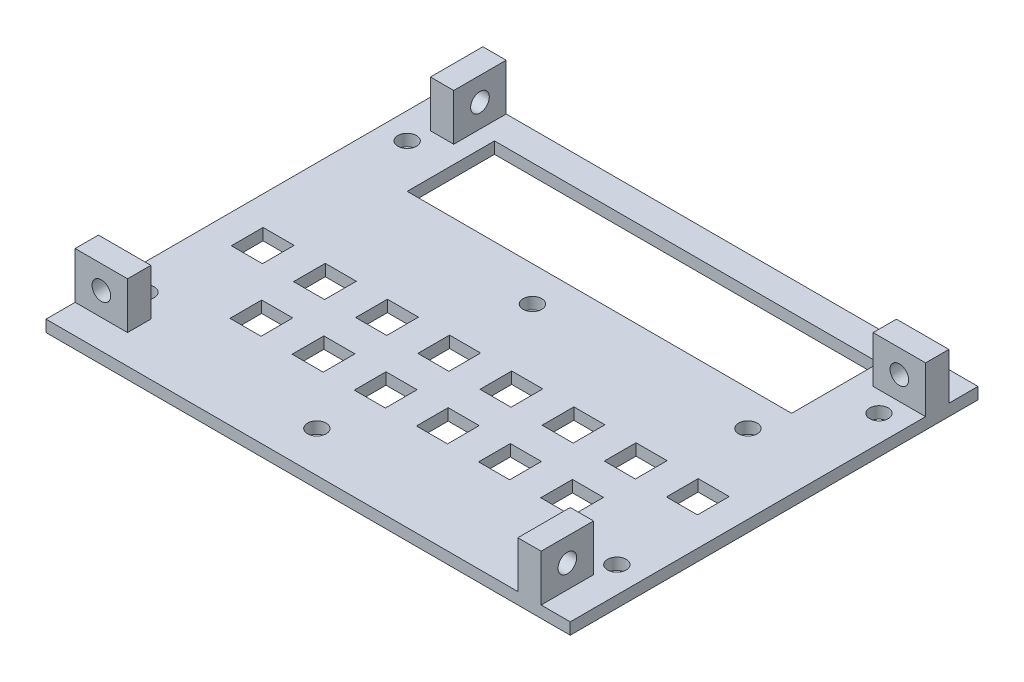
SolidWorks part; units mm, degrees
ref_plane "Plano frontal" through (0, 0, 0) normal (0, 0, 1) x (1, 0, 0)
ref_plane "Plano superior" through (0, 0, 0) normal (0, 1, 0) x (1, 0, 0)
ref_plane "Plano direito" through (0, 0, 0) normal (1, 0, 0) x (0, 0, -1)
sketch "Esboço1" plane through (0, 0, 0) normal (0, 1, 0) x (1, 0, 0)
  line L1 (-45, -35) -> (45, -35)
  line L2 (-45, -35) -> (-45, 35)
  line L3 (-45, 35) -> (45, 35)
  line L4 (45, -35) -> (45, 35)
  line L5 (-45, -35) -> (45, 35) construction
  line L6 (-45, 35) -> (45, -35) construction
  point P0 (0, 0)
  dimension "D1" = 90
  dimension "D2" = 70
extrude "Ressalto-extrusão1" add sketch "Esboço1" along normal blind 2
sketch "Esboço2" plane through (0, 2, 0) normal (0, 1, 0) x (1, 0, 0)
  line L104 (-29.33, -2.73) -> (-29.33, -8.18)
  line L105 (-23.996, -2.73) -> (-23.996, -8.18)
  line L106 (-29.33, -2.73) -> (-23.996, -2.73)
  line L107 (-29.33, -8.18) -> (-23.996, -8.18)
  line L108 (-18.66, -2.73) -> (-18.66, -8.18)
  line L109 (-13.326, -2.73) -> (-13.326, -8.18)
  line L110 (-18.66, -2.73) -> (-13.326, -2.73)
  line L111 (-18.66, -8.18) -> (-13.326, -8.18)
  line L112 (-7.99, -2.73) -> (-7.99, -8.18)
  line L113 (-2.656, -2.73) -> (-2.656, -8.18)
  line L114 (-7.99, -2.73) -> (-2.656, -2.73)
  line L115 (-7.99, -8.18) -> (-2.656, -8.18)
  line L116 (2.68, -2.73) -> (2.68, -8.18)
  line L117 (8.014, -2.73) -> (8.014, -8.18)
  line L118 (2.68, -2.73) -> (8.014, -2.73)
  line L119 (2.68, -8.18) -> (8.014, -8.18)
  line L120 (13.35, -2.73) -> (13.35, -8.18)
  line L121 (18.684, -2.73) -> (18.684, -8.18)
  line L122 (13.35, -2.73) -> (18.684, -2.73)
  line L123 (13.35, -8.18) -> (18.684, -8.18)
  line L124 (24.02, -2.73) -> (24.02, -8.18)
  line L125 (29.354, -2.73) -> (29.354, -8.18)
  line L126 (24.02, -2.73) -> (29.354, -2.73)
  line L127 (24.02, -8.18) -> (29.354, -8.18)
  line L128 (34.69, -2.73) -> (34.69, -8.18)
  line L129 (40.024, -2.73) -> (40.024, -8.18)
  line L130 (34.69, -2.73) -> (40.024, -2.73)
  line L131 (34.69, -8.18) -> (40.024, -8.18)
  line L132 (-29.33, -13.64) -> (-29.33, -19.09)
  line L133 (-23.996, -13.64) -> (-23.996, -19.09)
  line L134 (-29.33, -13.64) -> (-23.996, -13.64)
  line L135 (-29.33, -19.09) -> (-23.996, -19.09)
  line L136 (-18.66, -13.64) -> (-18.66, -19.09)
  line L137 (-13.326, -13.64) -> (-13.326, -19.09)
  line L138 (-18.66, -13.64) -> (-13.326, -13.64)
  line L139 (-18.66, -19.09) -> (-13.326, -19.09)
  line L140 (-7.99, -13.64) -> (-7.99, -19.09)
  line L141 (-2.656, -13.64) -> (-2.656, -19.09)
  line L142 (-7.99, -13.64) -> (-2.656, -13.64)
  line L143 (-7.99, -19.09) -> (-2.656, -19.09)
  line L144 (2.68, -13.64) -> (2.68, -19.09)
  line L145 (8.014, -13.64) -> (8.014, -19.09)
  line L146 (2.68, -13.64) -> (8.014, -13.64)
  line L147 (2.68, -19.09) -> (8.014, -19.09)
  line L148 (13.35, -13.64) -> (13.35, -19.09)
  line L149 (18.684, -13.64) -> (18.684, -19.09)
  line L150 (13.35, -13.64) -> (18.684, -13.64)
  line L151 (13.35, -19.09) -> (18.684, -19.09)
  line L152 (24.02, -13.64) -> (24.02, -19.09)
  line L153 (29.354, -13.64) -> (29.354, -19.09)
  line L154 (24.02, -13.64) -> (29.354, -13.64)
  line L155 (24.02, -19.09) -> (29.354, -19.09)
  line L196 (-40, -2.73) -> (-40, -8.18)
  line L197 (-34.666, -2.73) -> (-34.666, -8.18)
  line L198 (-40, -2.73) -> (-34.666, -2.73)
  line L199 (-40, -8.18) -> (-34.666, -8.18)
  point P0 (0, 0)
sketch "Esboço3" plane through (0, 2, 0) normal (0, 1, 0) x (1, 0, 0)
  line L5 (-40, 35) -> (-36, 35)
  line L7 (-40, 26) -> (-36, 26)
  line L8 (-36, 35) -> (-36, 26)
  line L42 (45, 30) -> (45, 26)
  line L43 (45, 26) -> (36, 26)
  line L44 (36, 30) -> (36, 26)
  line L51 (40, -26) -> (36, -26)
  line L52 (36, -35) -> (36, -26)
  line L58 (-45, -30) -> (-45, -26)
  line L59 (-45, -26) -> (-36, -26)
  line L60 (-36, -30) -> (-36, -26)
  line L63 (36, -35) -> (40, -35)
  line L68 (-40, 26) -> (-40, 35)
  line L69 (-36, -30) -> (-45, -30)
  line L70 (-45, -35) -> (45, -35) construction
  line L71 (40, -26) -> (40, -35)
  line L72 (45, -35) -> (45, 35) construction
  line L73 (36, 30) -> (45, 30)
  line L74 (45, 35) -> (-45, 35) construction
  dimension "D2" = 4
  dimension "D3" = 9
  dimension "D4" = 4
  dimension "D5" = 5
  dimension "D6" = 4
  dimension "D7" = 9
  dimension "D8" = 5
  dimension "D9" = 9
  dimension "D10" = 5
  dimension "D11" = 5
  dimension "D12" = 4
  dimension "D13" = 9
extrude "Ressalto-extrusão4" add sketch "Esboço3" along normal blind 8
sketch "Esboço6" plane through (0, 0, 0) normal (0, -1, 0) x (1, 0, 0)
  line L0 (0, 0) -> (0, -35) construction
  line L1 (45, -35) -> (-45, -35) construction
  line L3 (33, -30) -> (-33, -30)
  line L4 (33, -30) -> (33, -15)
  line L5 (33, -15) -> (-33, -15)
  line L6 (-33, -30) -> (-33, -15)
  line L7 (33, -30) -> (-33, -15) construction
  line L8 (33, -15) -> (-33, -30) construction
  point P5 (0, -22.5)
  dimension "D1" = 15
  dimension "D2" = 66
  dimension "D3" = 5
extrude "Corte-extrusão4" cut sketch "Esboço6" against normal blind 3
sketch "Esboço7" plane through (0, 2, 0) normal (0, 1, 0) x (1, 0, 0)
  line L1 (45, -35) -> (45, 26) construction
  line L3 (45, 35) -> (-36, 35) construction
  line L4 (31.5, 9) -> (-5.5, 9) construction
  line L5 (-5.5, 9) -> (-5.5, -28) construction
  line L6 (-5.5, -28) -> (31.5, -28) construction
  line L7 (31.5, -28) -> (31.5, 9) construction
  circle A0 centre (31.5, 9) radius 1.6
  circle A1 centre (-5.5, 9) radius 1.6
  circle A2 centre (-5.5, -28) radius 1.6
  circle A3 centre (31.5, -28) radius 1.6
  dimension "D1" = 3.2
  dimension "D6" = 3.2
  dimension "D7" = 3.2
  dimension "D8" = 3.2
  dimension "D2" = 13.5
  dimension "D3" = 26
  dimension "D4" = 37
  dimension "D5" = 37
extrude "Corte-extrusão7" cut sketch "Esboço7" against normal blind 3
sketch "Esboço8" plane through (0, 0, -30) normal (0, 0, -1) x (-1, 0, 0)
  line L0 (-40.5, 10) -> (-40.5, 2) construction
  line L1 (-45, 10) -> (-36, 10) construction
  line L2 (-45, 2) -> (-36, 2) construction
  circle A0 centre (-40.5, 6) radius 1.6
  dimension "D1" = 3.2
extrude "Corte-extrusão8" cut sketch "Esboço8" against normal blind 5
sketch "Esboço9" plane through (-40, 0, 0) normal (-1, 0, 0) x (0, 0, 1)
  line L0 (-30.5, 10) -> (-30.5, 2) construction
  line L1 (-35, 10) -> (-26, 10) construction
  line L2 (-35, 2) -> (-26, 2) construction
  circle A0 centre (-30.5, 6) radius 1.6
  dimension "D1" = 3.2
extrude "Corte-extrusão9" cut sketch "Esboço9" against normal blind 5
sketch "Esboço10" plane through (0, 0, 30) normal (0, 0, 1) x (1, 0, 0)
  line L0 (-40.5, 10) -> (-40.5, 2) construction
  line L1 (-45, 10) -> (-36, 10) construction
  line L2 (-45, 2) -> (-36, 2) construction
  circle A0 centre (-40.5, 6) radius 1.6
  dimension "D1" = 3.2
extrude "Corte-extrusão10" cut sketch "Esboço10" against normal blind 5
sketch "Esboço11" plane through (40, 0, 0) normal (1, 0, 0) x (0, 0, -1)
  line L0 (-30.5, 10) -> (-30.5, 2) construction
  line L1 (-35, 10) -> (-26, 10) construction
  line L2 (-35, 2) -> (-26, 2) construction
  circle A0 centre (-30.5, 6) radius 1.6
  dimension "D1" = 3.2
extrude "Corte-extrusão11" cut sketch "Esboço11" against normal blind 5
sketch "Esboço12" plane through (0, 2, 0) normal (0, 1, 0) x (1, 0, 0)
  line L0 (-45, 35) -> (-36, 35) construction
  line L1 (-40.5, 35) -> (-40.5, -35) construction
  line L2 (-45, -35) -> (36, -35) construction
  line L3 (45, 35) -> (36, 35) construction
  line L4 (45, 35) -> (-36, 35) construction
  line L5 (40.5, 35) -> (40.5, -35) construction
  line L6 (40, -35) -> (45, -35) construction
  circle A0 centre (-40.5, 22.5) radius 1.6
  circle A1 centre (-40.5, -22.5) radius 1.6
  circle A2 centre (40.5, -22.5) radius 1.6
  circle A3 centre (40.5, 22.5) radius 1.6
  dimension "D1" = 3.2
  dimension "D2" = 3.2
  dimension "D7" = 3.2
  dimension "D8" = 3.2
  dimension "D3" = 12.5
  dimension "D4" = 12.5
  dimension "D5" = 12.5
  dimension "D6" = 12.5
extrude "Corte-extrusão12" cut sketch "Esboço12" against normal through all
extrude "Corte-extrusão13" cut sketch "Esboço2" against normal through all
